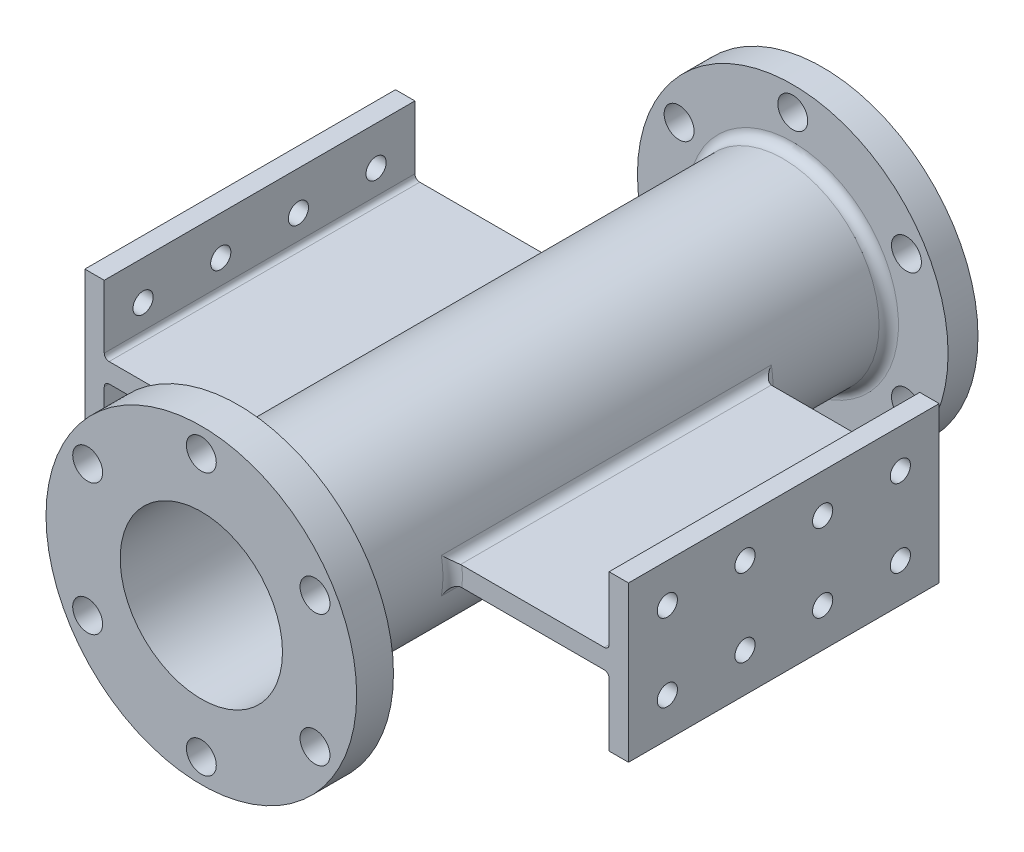
SolidWorks part; units mm, degrees
ref_plane "Front Plane" through (0, 0, 0) normal (0, 0, 1) x (1, 0, 0)
ref_plane "Top Plane" through (0, 0, 0) normal (0, 1, 0) x (1, 0, 0)
ref_plane "Right Plane" through (0, 0, 0) normal (1, 0, 0) x (0, 0, -1)
ref_axis "Axis1" through (0, 0, -88.99) along (0, 0, 1)
sketch "Sketch1" plane through (0, 0, 0) normal (0, 0, 1) x (1, 0, 0)
  circle A0 centre (0, 0) radius 50.8
  dimension "D1" = 101.6
extrude "Boss-Extrude1" add sketch "Sketch1" along normal mid plane 203.2 contours A0
sketch "Sketch2" plane through (0, 0, 0) normal (1, 0, 0) x (0, 0, -1)
  line L0 (-89.5604, 50.8) -> (-89.5604, 31.3944)
  line L1 (101.6, 50.8) -> (-101.6, 50.8) construction
  line L2 (-89.5604, 31.3944) -> (91.821, 31.3944)
  line L3 (91.821, 31.3944) -> (91.821, 50.8)
  line L4 (91.821, 50.8) -> (-89.5604, 50.8)
  line L5 (-101.6, 50.8) -> (-101.6, -50.8) construction
  line L6 (101.6, -50.8) -> (101.6, 50.8) construction
  line L7 (88.99, 0) -> (-88.99, 0) construction
  dimension "D1" = 12.0396
  dimension "D2" = 9.779
  dimension "D3" = 31.3944
revolve "Cut-Revolve1" cut sketch "Sketch2" angle 360 about axis through (0, 0, -88.99) along (0, 0, 1)
sketch "Sketch3" plane through (0, 0, 101.6) normal (0, 0, 1) x (1, 0, 0)
  circle A0 centre (0, 0) radius 26.543
  dimension "D1" = 53.086
extrude "Cut-Extrude1" cut sketch "Sketch3" against normal through all contours A0
sketch "Sketch4" plane through (0, 0, 101.6) normal (0, 0, 1) x (1, 0, 0)
  circle A0 centre (0, 42.926) radius 4.8895
  dimension "D1" = 42.926
extrude "Cut-Extrude2" cut sketch "Sketch4" against normal through all contours A0
pattern_circular "CirPattern1" count 6 over 360 about axis through (0, 0, 0) along (0, 0, 1) of "Cut-Extrude2"
fillet "Fillet1" radius 3.175 2 edges at (-31.3944, 0, 89.5604) (-31.3944, 0, -91.821)
sketch "Sketch5" plane through (0, 0, 0) normal (0, 0, 1) x (1, 0, 0)
  line L0 (28.9814, 3.175) -> (82.55, 3.175)
  line L1 (82.55, 3.175) -> (82.55, 25.4)
  line L2 (82.55, 25.4) -> (88.9, 25.4)
  line L3 (88.9, 25.4) -> (88.9, -25.4)
  line L4 (88.9, -25.4) -> (82.55, -25.4)
  line L5 (82.55, -25.4) -> (82.55, -3.175)
  line L6 (82.55, -3.175) -> (28.9814, -3.175)
  line L7 (28.9814, -3.175) -> (28.9814, 3.175)
  line L8 (0, -55.88) -> (0, 55.88) construction
  line L9 (-28.9814, -3.175) -> (-28.9814, 3.175)
  line L10 (-82.55, -3.175) -> (-28.9814, -3.175)
  line L11 (-82.55, -25.4) -> (-82.55, -3.175)
  line L12 (-88.9, -25.4) -> (-82.55, -25.4)
  line L13 (-88.9, 25.4) -> (-88.9, -25.4)
  line L14 (-82.55, 25.4) -> (-88.9, 25.4)
  line L15 (-82.55, 3.175) -> (-82.55, 25.4)
  line L16 (-28.9814, 3.175) -> (-82.55, 3.175)
  dimension "D1" = 3.175
  dimension "D2" = 6.35
  dimension "D3" = 88.9
  dimension "D4" = 6.35
  dimension "D5" = 25.4
  dimension "D6" = 50.8
  dimension "D7" = 28.9814
extrude "Boss-Extrude2" add sketch "Sketch5" along normal mid plane 101.6
sketch "Sketch6" plane through (88.9, 0, 0) normal (1, 0, 0) x (0, 0, -1)
  line L0 (-50.8, -25.4) -> (-50.8, 25.4) construction
  line L1 (-50.8, -25.4) -> (50.8, -25.4) construction
  circle A0 centre (-38.1, -12.7) radius 3.302
  dimension "D1" = 12.7
  dimension "D3" = 6.604
  dimension "D2" = 12.7
extrude "Cut-Extrude3" cut sketch "Sketch6" against normal up to next
pattern_linear "LPattern1" count 4 spacing 25.4 along (0, 0, -1) count 2 spacing 25.4 along (0, 1, 0) of "Cut-Extrude3"
sketch "Sketch7" plane through (-88.9, 0, 0) normal (-1, 0, 0) x (0, 0, 1)
  line L0 (50.8, 25.4) -> (50.8, -25.4) construction
  line L1 (50.8, -25.4) -> (-50.8, -25.4) construction
  circle A0 centre (38.1, -12.7) radius 3.302
  dimension "D3" = 6.604
  dimension "D1" = 12.7
  dimension "D2" = 12.7
extrude "Cut-Extrude4" cut sketch "Sketch7" against normal up to next
pattern_linear "LPattern2" count 4 spacing 25.4 along (0, 0, -1) count 2 spacing 25.4 along (0, 1, 0) of "Cut-Extrude4"
fillet "Fillet2" radius 1.5875 4 edges at (-82.55, -3.175, 0) (-82.55, 3.175, 0) (82.55, 3.175, 0) (82.55, -3.175, 0)
fillet "Fillet3" radius 3.175 8 edges at (-31.3944, 0, 50.8) (-31.2334, -3.175, 0) (-31.3944, 0, -50.8) (-31.2334, 3.175, 0) (31.3944, 0, -50.8) (31.2334, -3.175, 0) (31.3944, 0, 50.8) (31.2334, 3.175, 0)
